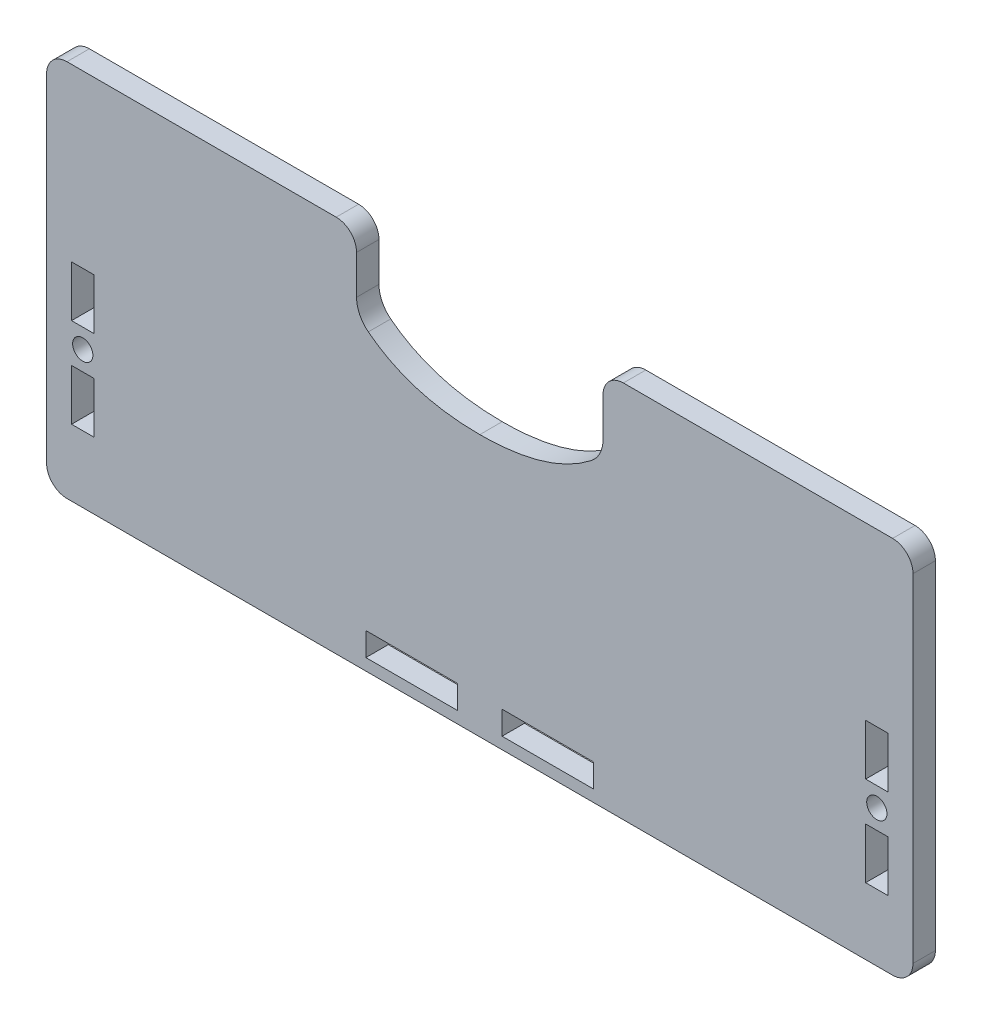
SolidWorks part; units mm, degrees
ref_plane "Front Plane" through (0, 0, 0) normal (0, 0, 1) x (1, 0, 0)
ref_plane "Top Plane" through (0, 0, 0) normal (0, 1, 0) x (1, 0, 0)
ref_plane "Right Plane" through (0, 0, 0) normal (1, 0, 0) x (0, 0, -1)
sketch "Sketch1" plane through (0, 0, 0) normal (0, 0, 1) x (1, 0, 0)
  line L0 (-108.0486, 85.6) -> (-30.7376, 85.6)
  line L1 (-108.0486, 85.6) -> (-108.0486, 0)
  line L2 (-30.7376, 85.6) -> (-30.7376, 67.3941)
  line L3 (30.7376, 85.6) -> (108.0486, 85.6)
  line L4 (30.7376, 85.6) -> (30.7376, 67.3941)
  line L5 (-108.0486, 0) -> (108.0486, 0)
  line L6 (108.0486, 85.6) -> (108.0486, 0)
  line L7 (15.7308, 56.5325) -> (-15.7308, 56.5325) construction
  spline S0 degree 2 poles (-30.7376, 67.3941) (-19.6635, 56.5325) (0, 56.5325) knots 0 0 0 1 1 1
  spline S1 degree 2 poles (30.7376, 67.3941) (19.6635, 56.5325) (0, 56.5325) knots 0 0 0 1 1 1
  dimension "D1" = 61.4751
  dimension "D2" = 216.0971
  dimension "D3" = 85.6
extrude "Boss-Extrude1" add sketch "Sketch1" along normal blind 5.588
fillet "Fillet1" radius 5.08 6 edges at (108.0486, 0, 2.794) (108.0486, 85.6, 2.794) (-108.0486, 85.6, 2.794) (30.7376, 85.6, 2.794) (-30.7376, 85.6, 2.794) (-108.0486, 0, 2.794)
fillet "Fillet3" radius 7.62 2 edges at (30.7376, 67.3941, 2.794) (-30.7376, 67.3941, 2.794)
sketch "Sketch3" plane through (0, 0, 0) normal (0, 0, 1) x (1, 0, 0)
  line L0 (-101.8256, 14.2083) -> (101.8256, 14.2083) construction
  line L1 (-96.2376, 7.8583) -> (-101.8256, 7.8583)
  line L2 (-96.2376, 7.8583) -> (-96.2376, 20.5583)
  line L3 (-96.2376, 20.5583) -> (-101.8256, 20.5583)
  line L4 (-101.8256, 7.8583) -> (-101.8256, 20.5583)
  line L5 (101.8256, 7.8583) -> (96.2376, 7.8583)
  line L6 (101.8256, 7.8583) -> (101.8256, 20.5583)
  line L7 (101.8256, 20.5583) -> (96.2376, 20.5583)
  line L8 (96.2376, 7.8583) -> (96.2376, 20.5583)
  line L9 (0, 0) -> (0, 14.2083) construction
  line L10 (-102.9686, 0) -> (102.9686, 0) construction
  line L11 (-99.0316, 20.5583) -> (-99.0316, 25.4) construction
  line L12 (99.0316, 20.5583) -> (99.0316, 25.4) construction
  line L13 (-99.0316, 25.4) -> (-99.0316, 30.2417) construction
  line L14 (-101.8256, 42.9417) -> (-96.2376, 42.9417)
  line L15 (-101.8256, 42.9417) -> (-101.8256, 30.2417)
  line L16 (-101.8256, 30.2417) -> (-96.2376, 30.2417)
  line L17 (-96.2376, 42.9417) -> (-96.2376, 30.2417)
  line L18 (-101.8256, 42.9417) -> (-96.2376, 30.2417) construction
  line L19 (-101.8256, 30.2417) -> (-96.2376, 42.9417) construction
  line L20 (99.0316, 25.4) -> (99.0316, 30.2417) construction
  line L21 (96.2376, 30.2417) -> (101.8256, 30.2417)
  line L22 (96.2376, 30.2417) -> (96.2376, 42.9417)
  line L23 (96.2376, 42.9417) -> (101.8256, 42.9417)
  line L24 (101.8256, 30.2417) -> (101.8256, 42.9417)
  circle A0 centre (-99.0316, 25.4) radius 2.5273
  circle A1 centre (99.0316, 25.4) radius 2.5273
  point P21 (-99.0316, 36.5917)
  dimension "D6" = 5.0546
  dimension "D1" = 12.7
  dimension "D2" = 5.588
  dimension "D3" = 192.4751
  dimension "D4" = 7.8583
  dimension "D5" = 25.4
extrude "Cut-Extrude2" cut sketch "Sketch3" along normal through all
sketch "Sketch5" plane through (0, 0, 5.588) normal (0, 0, 1) x (1, 0, 0)
  line L0 (-108.0486, 5.08) -> (-108.0486, -3.683)
  line L1 (-102.9686, -8.763) -> (102.9686, -8.763)
  line L2 (108.0486, -3.683) -> (108.0486, 5.08)
  line L3 (-102.9686, 0) -> (102.9686, 0) construction
  line L4 (-102.9686, 0) -> (102.9686, 0)
  line L5 (-5.5562, -2.921) -> (5.5563, -2.921) construction
  line L6 (-28.4162, 0) -> (-5.5562, 0)
  line L7 (-28.4162, 0) -> (-28.4162, -5.842)
  line L8 (-28.4162, -5.842) -> (-5.5562, -5.842)
  line L9 (-5.5562, 0) -> (-5.5562, -5.842)
  line L10 (5.5563, 0) -> (28.4162, 0)
  line L11 (5.5563, 0) -> (5.5563, -5.842)
  line L12 (5.5563, -5.842) -> (28.4162, -5.842)
  line L13 (28.4162, 0) -> (28.4162, -5.842)
  line L14 (0, -2.921) -> (0, 0) construction
  arc A0 (102.9686, -8.763) -> (108.0486, -3.683) centre (102.9686, -3.683) ccw
  arc A1 (-108.0486, -3.683) -> (-102.9686, -8.763) centre (-102.9686, -3.683) ccw
  arc A2 (-108.0486, 5.08) -> (-102.9686, 0) centre (-102.9686, 5.08) ccw construction
  arc A3 (102.9686, 0) -> (108.0486, 5.08) centre (102.9686, 5.08) ccw construction
  arc A4 (-108.0486, 5.08) -> (-102.9686, 0) centre (-102.9686, 5.08) ccw
  arc A5 (102.9686, 0) -> (108.0486, 5.08) centre (102.9686, 5.08) ccw
  arc M11 (-108.0486, 5.08) -> (-102.9686, 0) centre (-102.9686, 5.08) ccw
  line M12 (-102.9686, 0) -> (102.9686, 0)
  arc M13 (102.9686, 0) -> (108.0486, 5.08) centre (102.9686, 5.08) ccw
  dimension "D1" = 5.08
  dimension "D2" = 8.763
  dimension "D3" = 5.842
  dimension "D5" = 22.86
  dimension "D6" = 11.1125
extrude "Boss-Extrude3" add sketch "Sketch5" against normal up to surface (5.588 mm away) contours L0 A1 L1 A0 L2 L13 L12 L11 L9 L8 L7 M13 M12 M11 up to face at (-99.0316, 36.5917, 0)
